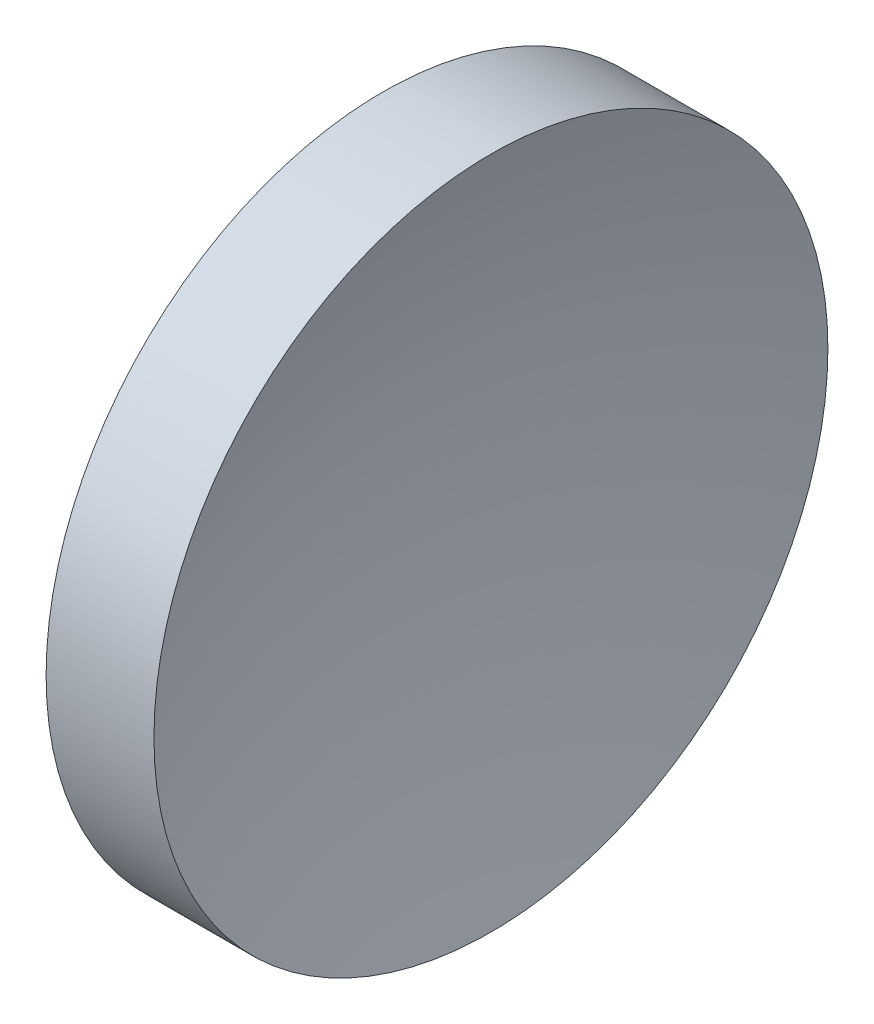
SolidWorks part; units mm, degrees
ref_plane "Plan de face" through (0, 0, 0) normal (0, 0, 1) x (1, 0, 0)
ref_plane "Plan de dessus" through (0, 0, 0) normal (0, 1, 0) x (1, 0, 0)
ref_plane "Plan de droite" through (0, 0, 0) normal (1, 0, 0) x (0, 0, -1)
ref_plane "Plan3" through (0, 10, 0) normal (0, 1, 0) x (-1, 0, 0)
sketch "Esquisse11" plane through (0, 0, 0) normal (0, 1, 0) x (1, 0, 0)
  line L0 (1.9967, 0) -> (-35.5294, 0) construction
  line L1 (1.9967, 0) -> (1.9967, -18.8599) construction
  line L2 (4, -12.5) -> (0, -12.5)
  line L3 (1.9967, 0) -> (-0.5217, 0)
  line L4 (1.9967, 0) -> (153.2438, 0) construction
  line L5 (0, -12.5) -> (0, 0) construction
  arc A0 (4, -12.5) -> (1.9967, 0) centre (41.9967, 0) cw
  arc A1 (-0.5217, 0) -> (0, -12.5) centre (149.4783, 0) ccw
  point P11 (1.9967, -7.7348)
  dimension "D2" = 40
  dimension "D4" = 150
  dimension "D1" = 25
  dimension "D3" = 4
revolve "Révolution3" add sketch "Esquisse11" angle 360 about L0
